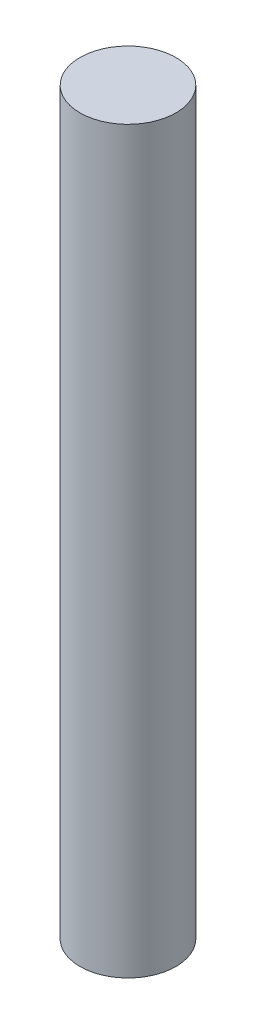
SolidWorks part; units mm, degrees
ref_plane "Piano frontale" through (0, 0, 0) normal (0, 0, 1) x (1, 0, 0)
ref_plane "Piano superiore" through (0, 0, 0) normal (0, 1, 0) x (1, 0, 0)
ref_plane "Piano destro" through (0, 0, 0) normal (1, 0, 0) x (0, 0, -1)
sketch "Sketch1" plane through (0, 0, 0) normal (0, 1, 0) x (1, 0, 0)
  circle A0 centre (0, 0) radius 4.75
extrude "Boss-Extrude1" add sketch "Sketch1" along normal blind 73.2
